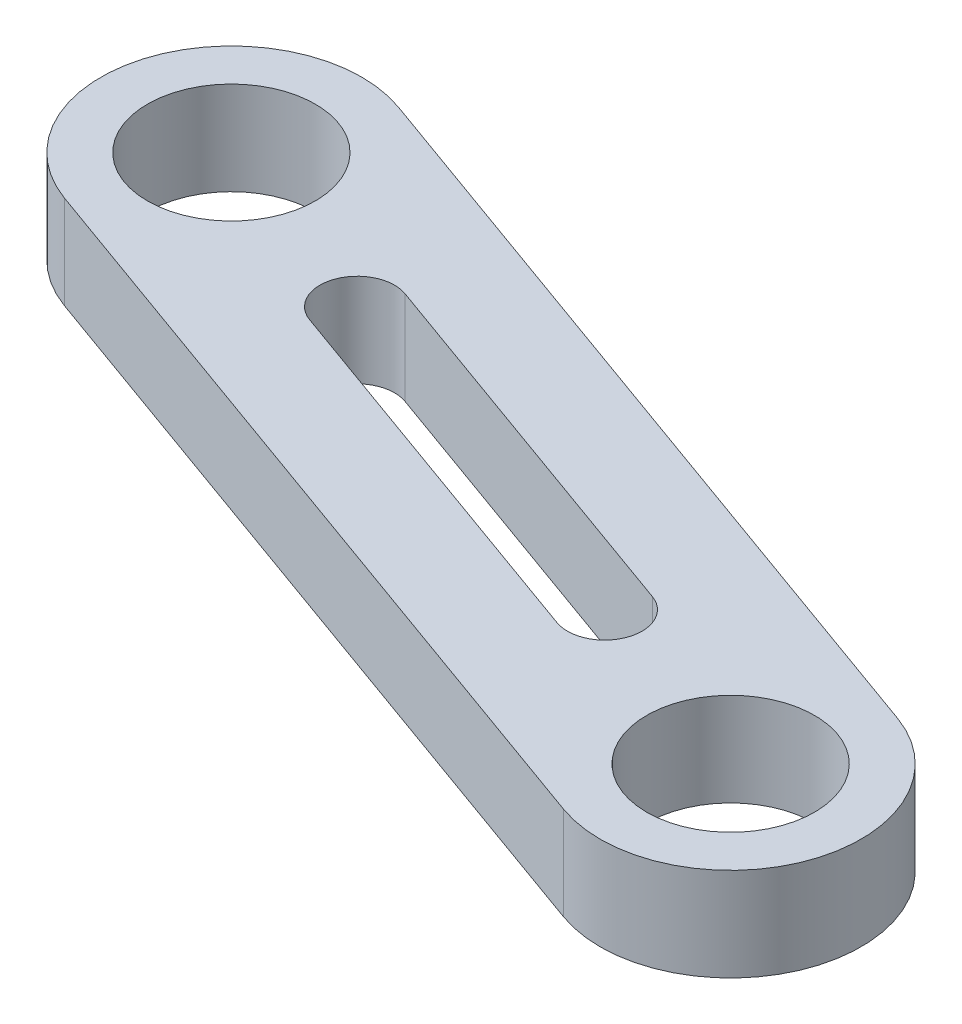
SolidWorks part; units mm, degrees
material "Thornel Mat VMA"
ref_plane "前视基准面" through (0, 0, 0) normal (0, 0, 1) x (1, 0, 0)
ref_plane "上视基准面" through (0, 0, 0) normal (0, 1, 0) x (1, 0, 0)
ref_plane "右视基准面" through (0, 0, 0) normal (1, 0, 0) x (0, 0, -1)
other "Configuration Table"
sketch "草图1" plane through (0, 0, 0) normal (0, 1, 0) x (1, 0, 0)
  line L0 (-41.7689, -100) -> (0, -115) construction
  line L1 (-41.7689, -100) -> (0, -115) construction
  line L2 (-39.403, -93.4119) -> (2.3659, -108.4119)
  line L3 (-44.1348, -106.5881) -> (-2.3659, -121.5881)
  circle A0 centre (0, -115) radius 9 construction
  circle A1 centre (14.8778, -73.5916) radius 44 construction
  circle A2 centre (-49, -6) radius 49 construction
  circle A3 centre (14.8778, -73.5916) radius 62.5 construction
  circle A4 centre (-41.7689, -100) radius 5 construction
  arc A5 (-39.403, -93.4119) -> (-44.1348, -106.5881) centre (-41.7689, -100) ccw
  arc A6 (-2.3659, -121.5881) -> (2.3659, -108.4119) centre (0, -115) ccw
  circle A7 centre (-41.7689, -100) radius 4.5
  circle A8 centre (0, -115) radius 4.5
  point P10 (-20.8845, -107.5)
  dimension "D2" = 18
  dimension "D3" = 88
  dimension "D4" = 98
  dimension "D7" = 125
  dimension "D9" = 10
  dimension "D10" = 7
  dimension "D11" = 9
  dimension "D1" = 115
  dimension "D5" = 6
  dimension "D6" = 49
  dimension "D8" = 100
extrude "凸台-拉伸1" add sketch "草图1" along normal blind 5
sketch "草图2" plane through (0, 5, 0) normal (0, 1, 0) x (1, 0, 0)
  line L0 (-41.7689, -100) -> (0, -115) construction
  line L1 (-31.2371, -103.7822) -> (-10.5318, -111.2178) construction
  line L2 (-30.5612, -101.8999) -> (-9.8558, -109.3355)
  line L3 (-31.9131, -105.6645) -> (-11.2078, -113.1001)
  arc A0 (-30.5612, -101.8999) -> (-31.9131, -105.6645) centre (-31.2371, -103.7822) ccw
  arc A1 (-11.2078, -113.1001) -> (-9.8558, -109.3355) centre (-10.5318, -111.2178) ccw
  point P6 (-20.8845, -107.5)
  point P13 (-20.8845, -107.5)
  dimension "D1" = 2
  dimension "D2" = 22
extrude "切除-拉伸1" cut sketch "草图2" against normal blind 10
